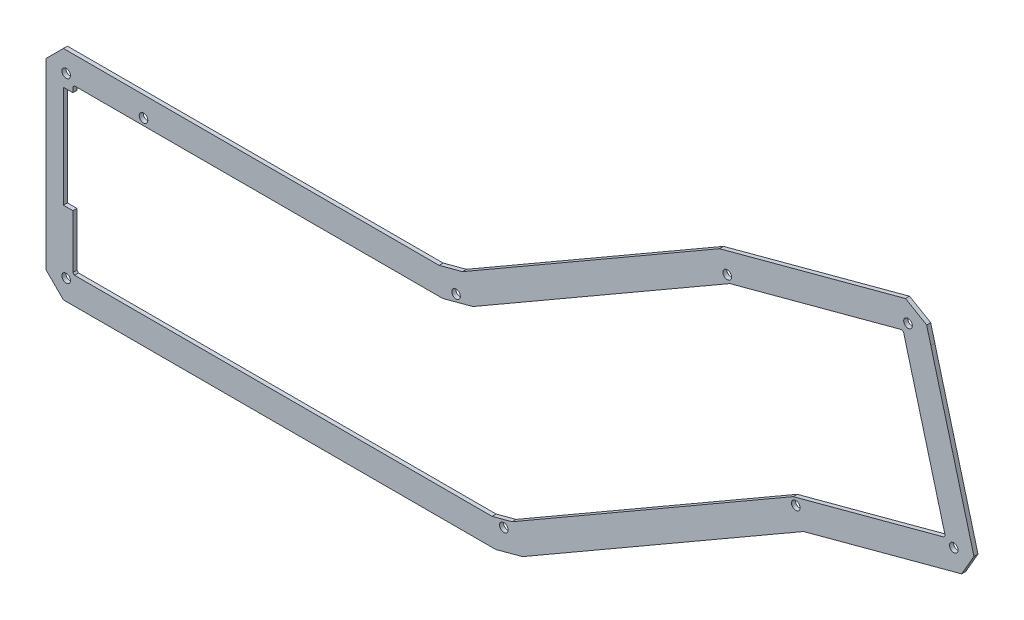
SolidWorks part; units mm, degrees
ref_plane "Plan de face" through (0, 0, 0) normal (0, 0, 1) x (1, 0, 0)
ref_plane "Plan de dessus" through (0, 0, 0) normal (0, 1, 0) x (1, 0, 0)
ref_plane "Plan de droite" through (0, 0, 0) normal (1, 0, 0) x (0, 0, -1)
sketch "Esquisse1" plane through (0, 0, 0) normal (0, 0, 1) x (1, 0, 0)
  line L0 (-73.9886, 18.0851) -> (-59.9886, 18.0851) construction
  line L1 (-73.9886, 37.0851) -> (-59.9886, 37.0851) construction
  line L2 (-73.9886, 37.0851) -> (-73.9886, 23.0851) construction
  line L3 (-73.9886, 23.0851) -> (-59.9886, 23.0851) construction
  line L4 (-59.9886, 37.0851) -> (-59.9886, 23.0851) construction
  line L5 (-73.9886, 18.0851) -> (-73.9886, 4.0851) construction
  line L6 (-73.9886, 4.0851) -> (-59.9886, 4.0851) construction
  line L7 (-59.9886, 18.0851) -> (-59.9886, 4.0851) construction
  line L8 (-73.9886, -0.9149) -> (-59.9886, -0.9149) construction
  line L9 (-73.9886, -0.9149) -> (-73.9886, -14.9149) construction
  line L10 (-73.9886, -14.9149) -> (-59.9886, -14.9149) construction
  line L11 (-59.9886, -0.9149) -> (-59.9886, -14.9149) construction
  line L12 (-73.9886, 37.0851) -> (-73.9886, 18.0851) construction
  line L13 (-54.9886, 18.0851) -> (-40.9886, 18.0851) construction
  line L14 (-54.9886, 37.0851) -> (-40.9886, 37.0851) construction
  line L15 (-54.9886, 37.0851) -> (-54.9886, 23.0851) construction
  line L16 (-54.9886, 23.0851) -> (-40.9886, 23.0851) construction
  line L17 (-40.9886, 37.0851) -> (-40.9886, 23.0851) construction
  line L18 (-54.9886, 18.0851) -> (-54.9886, 4.0851) construction
  line L19 (-54.9886, 4.0851) -> (-40.9886, 4.0851) construction
  line L20 (-40.9886, 18.0851) -> (-40.9886, 4.0851) construction
  line L21 (-54.9886, -0.9149) -> (-40.9886, -0.9149) construction
  line L22 (-54.9886, -0.9149) -> (-54.9886, -14.9149) construction
  line L23 (-54.9886, -14.9149) -> (-40.9886, -14.9149) construction
  line L24 (-40.9886, -0.9149) -> (-40.9886, -14.9149) construction
  line L25 (-54.9886, 37.0851) -> (-54.9886, 18.0851) construction
  line L26 (-35.9886, 18.0851) -> (-21.9886, 18.0851) construction
  line L27 (-35.9886, 37.0851) -> (-21.9886, 37.0851) construction
  line L28 (-35.9886, 37.0851) -> (-35.9886, 23.0851) construction
  line L29 (-35.9886, 23.0851) -> (-21.9886, 23.0851) construction
  line L30 (-21.9886, 37.0851) -> (-21.9886, 23.0851) construction
  line L31 (-35.9886, 18.0851) -> (-35.9886, 4.0851) construction
  line L32 (-35.9886, 4.0851) -> (-21.9886, 4.0851) construction
  line L33 (-21.9886, 18.0851) -> (-21.9886, 4.0851) construction
  line L34 (-35.9886, -0.9149) -> (-21.9886, -0.9149) construction
  line L35 (-35.9886, -0.9149) -> (-35.9886, -14.9149) construction
  line L36 (-35.9886, -14.9149) -> (-21.9886, -14.9149) construction
  line L37 (-21.9886, -0.9149) -> (-21.9886, -14.9149) construction
  line L38 (-35.9886, 37.0851) -> (-35.9886, 18.0851) construction
  line L39 (-16.9886, 18.0851) -> (-2.9886, 18.0851) construction
  line L40 (-16.9886, 37.0851) -> (-2.9886, 37.0851) construction
  line L41 (-16.9886, 37.0851) -> (-16.9886, 23.0851) construction
  line L42 (-16.9886, 23.0851) -> (-2.9886, 23.0851) construction
  line L43 (-2.9886, 37.0851) -> (-2.9886, 23.0851) construction
  line L44 (-16.9886, 18.0851) -> (-16.9886, 4.0851) construction
  line L45 (-16.9886, 4.0851) -> (-2.9886, 4.0851) construction
  line L46 (-2.9886, 18.0851) -> (-2.9886, 4.0851) construction
  line L47 (-16.9886, -0.9149) -> (-2.9886, -0.9149) construction
  line L48 (-16.9886, -0.9149) -> (-16.9886, -14.9149) construction
  line L49 (-16.9886, -14.9149) -> (-2.9886, -14.9149) construction
  line L50 (-2.9886, -0.9149) -> (-2.9886, -14.9149) construction
  line L51 (-16.9886, 37.0851) -> (-16.9886, 18.0851) construction
  line L52 (2.0114, 18.0851) -> (16.0114, 18.0851) construction
  line L53 (2.0114, 37.0851) -> (16.0114, 37.0851) construction
  line L54 (2.0114, 37.0851) -> (2.0114, 23.0851) construction
  line L55 (2.0114, 23.0851) -> (16.0114, 23.0851) construction
  line L56 (16.0114, 37.0851) -> (16.0114, 23.0851) construction
  line L57 (2.0114, 18.0851) -> (2.0114, 4.0851) construction
  line L58 (2.0114, 4.0851) -> (16.0114, 4.0851) construction
  line L59 (16.0114, 18.0851) -> (16.0114, 4.0851) construction
  line L60 (2.0114, -0.9149) -> (16.0114, -0.9149) construction
  line L61 (2.0114, -0.9149) -> (2.0114, -14.9149) construction
  line L62 (2.0114, -14.9149) -> (16.0114, -14.9149) construction
  line L63 (16.0114, -0.9149) -> (16.0114, -14.9149) construction
  line L64 (2.0114, 37.0851) -> (2.0114, 18.0851) construction
  line L65 (21.0114, 18.0851) -> (35.0114, 18.0851) construction
  line L66 (21.0114, 37.0851) -> (35.0114, 37.0851) construction
  line L67 (21.0114, 37.0851) -> (21.0114, 23.0851) construction
  line L68 (21.0114, 23.0851) -> (35.0114, 23.0851) construction
  line L69 (35.0114, 37.0851) -> (35.0114, 23.0851) construction
  line L70 (21.0114, 18.0851) -> (21.0114, 4.0851) construction
  line L71 (21.0114, 4.0851) -> (35.0114, 4.0851) construction
  line L72 (35.0114, 18.0851) -> (35.0114, 4.0851) construction
  line L73 (21.0114, -0.9149) -> (35.0114, -0.9149) construction
  line L74 (21.0114, -0.9149) -> (21.0114, -14.9149) construction
  line L75 (21.0114, -14.9149) -> (35.0114, -14.9149) construction
  line L76 (35.0114, -0.9149) -> (35.0114, -14.9149) construction
  line L77 (21.0114, 37.0851) -> (21.0114, 18.0851) construction
  line L78 (40.0114, 18.0851) -> (54.0114, 18.0851) construction
  line L79 (40.0114, 37.0851) -> (54.0114, 37.0851) construction
  line L80 (40.0114, 37.0851) -> (40.0114, 23.0851) construction
  line L81 (40.0114, 23.0851) -> (54.0114, 23.0851) construction
  line L82 (54.0114, 37.0851) -> (54.0114, 23.0851) construction
  line L83 (40.0114, 18.0851) -> (40.0114, 4.0851) construction
  line L84 (40.0114, 4.0851) -> (54.0114, 4.0851) construction
  line L85 (54.0114, 18.0851) -> (54.0114, 4.0851) construction
  line L86 (40.0114, -0.9149) -> (54.0114, -0.9149) construction
  line L87 (40.0114, -0.9149) -> (40.0114, -14.9149) construction
  line L88 (40.0114, -14.9149) -> (54.0114, -14.9149) construction
  line L89 (54.0114, -0.9149) -> (54.0114, -14.9149) construction
  line L90 (40.0114, 37.0851) -> (40.0114, 18.0851) construction
  line L91 (-73.9886, 18.0851) -> (-54.9886, 18.0851) construction
  line L92 (56.0114, 20.0851) -> (56.7532, 18.8002) construction
  line L93 (38.0114, 39.0851) -> (56.0114, 39.0851) construction
  line L94 (56.0114, 39.0851) -> (56.0114, 21.0851) construction
  line L95 (38.0114, 21.0851) -> (56.0114, 21.0851) construction
  line L96 (38.0114, 39.0851) -> (38.0114, 21.0851) construction
  line L97 (19.0114, 39.0851) -> (37.0114, 39.0851) construction
  line L98 (37.0114, 39.0851) -> (37.0114, 21.0851) construction
  line L99 (19.0114, 21.0851) -> (37.0114, 21.0851) construction
  line L100 (19.0114, 39.0851) -> (19.0114, 21.0851) construction
  line L101 (79.4363, 55.512) -> (88.4363, 39.9235) construction
  line L102 (88.4363, 39.9235) -> (72.8478, 30.9235) construction
  line L103 (63.8478, 46.512) -> (72.8478, 30.9235) construction
  line L104 (79.4363, 55.512) -> (63.8478, 46.512) construction
  line L105 (62.9818, 46.012) -> (71.9818, 30.4235) construction
  line L106 (71.9818, 30.4235) -> (56.3933, 21.4235) construction
  line L107 (47.3933, 37.012) -> (56.3933, 21.4235) construction
  line L108 (62.9818, 46.012) -> (47.3933, 37.012) construction
  line L109 (164.2542, 60.603) -> (148.6657, 51.603) construction
  line L110 (62.2497, 43.2799) -> (71.7497, 26.8254) construction
  line L111 (78.7042, 52.7799) -> (88.2042, 36.3254) construction
  line L112 (95.1587, 62.2799) -> (104.6587, 45.8254) construction
  line L113 (111.6132, 71.7799) -> (121.1132, 55.3254) construction
  line L114 (128.0677, 81.2799) -> (137.5677, 64.8254) construction
  line L115 (144.5221, 90.7799) -> (154.0221, 74.3254) construction
  line L116 (148.6657, 51.603) -> (157.6657, 36.0146) construction
  line L117 (69.1254, 3.371) -> (76.1254, -8.7534) construction
  line L118 (88.2497, -1.7534) -> (76.1254, -8.7534) construction
  line L119 (81.2497, 10.371) -> (88.2497, -1.7534) construction
  line L120 (81.2497, 10.371) -> (69.1254, 3.371) construction
  line L121 (59.6254, 19.8254) -> (66.6254, 7.7011) construction
  line L122 (78.7497, 14.7011) -> (66.6254, 7.7011) construction
  line L123 (71.7497, 26.8254) -> (78.7497, 14.7011) construction
  line L124 (50.1254, 36.2799) -> (57.1254, 24.1556) construction
  line L125 (69.2497, 31.1556) -> (57.1254, 24.1556) construction
  line L126 (62.2497, 43.2799) -> (69.2497, 31.1556) construction
  line L127 (62.2497, 43.2799) -> (50.1254, 36.2799) construction
  line L128 (71.7497, 26.8254) -> (59.6254, 19.8254) construction
  line L129 (85.5799, 12.871) -> (92.5799, 0.7466) construction
  line L130 (104.7042, 7.7466) -> (92.5799, 0.7466) construction
  line L131 (97.7042, 19.871) -> (104.7042, 7.7466) construction
  line L132 (97.7042, 19.871) -> (85.5799, 12.871) construction
  line L133 (76.0799, 29.3254) -> (83.0799, 17.2011) construction
  line L134 (95.2042, 24.2011) -> (83.0799, 17.2011) construction
  line L135 (88.2042, 36.3254) -> (95.2042, 24.2011) construction
  line L136 (66.5799, 45.7799) -> (73.5799, 33.6556) construction
  line L137 (85.7042, 40.6556) -> (73.5799, 33.6556) construction
  line L138 (78.7042, 52.7799) -> (85.7042, 40.6556) construction
  line L139 (78.7042, 52.7799) -> (66.5799, 45.7799) construction
  line L140 (88.2042, 36.3254) -> (76.0799, 29.3254) construction
  line L141 (102.0343, 22.371) -> (109.0343, 10.2466) construction
  line L142 (121.1587, 17.2466) -> (109.0343, 10.2466) construction
  line L143 (114.1587, 29.371) -> (121.1587, 17.2466) construction
  line L144 (114.1587, 29.371) -> (102.0343, 22.371) construction
  line L145 (92.5343, 38.8254) -> (99.5343, 26.7011) construction
  line L146 (111.6587, 33.7011) -> (99.5343, 26.7011) construction
  line L147 (104.6587, 45.8254) -> (111.6587, 33.7011) construction
  line L148 (83.0343, 55.2799) -> (90.0343, 43.1556) construction
  line L149 (102.1587, 50.1556) -> (90.0343, 43.1556) construction
  line L150 (95.1587, 62.2799) -> (102.1587, 50.1556) construction
  line L151 (95.1587, 62.2799) -> (83.0343, 55.2799) construction
  line L152 (104.6587, 45.8254) -> (92.5343, 38.8254) construction
  line L153 (118.4888, 31.871) -> (125.4888, 19.7466) construction
  line L154 (137.6132, 26.7466) -> (125.4888, 19.7466) construction
  line L155 (130.6132, 38.871) -> (137.6132, 26.7466) construction
  line L156 (130.6132, 38.871) -> (118.4888, 31.871) construction
  line L157 (108.9888, 48.3254) -> (115.9888, 36.2011) construction
  line L158 (128.1132, 43.2011) -> (115.9888, 36.2011) construction
  line L159 (121.1132, 55.3254) -> (128.1132, 43.2011) construction
  line L160 (99.4888, 64.7799) -> (106.4888, 52.6556) construction
  line L161 (118.6132, 59.6556) -> (106.4888, 52.6556) construction
  line L162 (111.6132, 71.7799) -> (118.6132, 59.6556) construction
  line L163 (111.6132, 71.7799) -> (99.4888, 64.7799) construction
  line L164 (121.1132, 55.3254) -> (108.9888, 48.3254) construction
  line L165 (134.9433, 41.371) -> (141.9433, 29.2466) construction
  line L166 (154.0677, 36.2466) -> (141.9433, 29.2466) construction
  line L167 (147.0677, 48.371) -> (154.0677, 36.2466) construction
  line L168 (147.0677, 48.371) -> (134.9433, 41.371) construction
  line L169 (125.4433, 57.8254) -> (132.4433, 45.7011) construction
  line L170 (144.5677, 52.7011) -> (132.4433, 45.7011) construction
  line L171 (137.5677, 64.8254) -> (144.5677, 52.7011) construction
  line L172 (115.9433, 74.2799) -> (122.9433, 62.1556) construction
  line L173 (135.0677, 69.1556) -> (122.9433, 62.1556) construction
  line L174 (128.0677, 81.2799) -> (135.0677, 69.1556) construction
  line L175 (128.0677, 81.2799) -> (115.9433, 74.2799) construction
  line L176 (137.5677, 64.8254) -> (125.4433, 57.8254) construction
  line L177 (151.3978, 50.871) -> (158.3978, 38.7466) construction
  line L178 (170.5221, 45.7466) -> (158.3978, 38.7466) construction
  line L179 (163.5221, 57.871) -> (170.5221, 45.7466) construction
  line L180 (163.5221, 57.871) -> (151.3978, 50.871) construction
  line L181 (141.8978, 67.3254) -> (148.8978, 55.2011) construction
  line L182 (161.0221, 62.2011) -> (148.8978, 55.2011) construction
  line L183 (154.0221, 74.3254) -> (161.0221, 62.2011) construction
  line L184 (132.3978, 83.7799) -> (139.3978, 71.6556) construction
  line L185 (151.5221, 78.6556) -> (139.3978, 71.6556) construction
  line L186 (144.5221, 90.7799) -> (151.5221, 78.6556) construction
  line L187 (144.5221, 90.7799) -> (132.3978, 83.7799) construction
  line L188 (154.0221, 74.3254) -> (141.8978, 67.3254) construction
  line L189 (173.2542, 45.0146) -> (157.6657, 36.0146) construction
  line L190 (164.2542, 60.603) -> (173.2542, 45.0146) construction
  line L191 (178.3169, 34.0986) -> (169.0534, 56.4627) construction
  line L192 (169.5193, 62.7839) -> (174.1781, 45.3972) construction
  line L193 (174.1781, 45.3972) -> (191.5647, 50.056) construction
  line L194 (186.906, 67.4426) -> (191.5647, 50.056) construction
  line L195 (162.1337, 98.0749) -> (167.0513, 79.7223) construction
  line L196 (169.5193, 62.7839) -> (186.906, 67.4426) construction
  line L197 (167.0513, 79.7223) -> (180.5742, 83.3457) construction
  line L198 (162.1337, 98.0749) -> (175.6567, 101.6983) construction
  line L199 (162.1337, 98.0749) -> (165.7572, 84.5519) construction
  line L200 (165.7572, 84.5519) -> (179.2801, 88.1754) construction
  line L201 (175.6567, 101.6983) -> (179.2801, 88.1754) construction
  line L202 (167.0513, 79.7223) -> (170.6747, 66.1993) construction
  line L203 (170.6747, 66.1993) -> (184.1977, 69.8228) construction
  line L204 (180.5742, 83.3457) -> (184.1977, 69.8228) construction
  line L205 (171.9688, 61.3697) -> (185.4918, 64.9932) construction
  line L206 (171.9688, 61.3697) -> (175.5923, 47.8467) construction
  line L207 (175.5923, 47.8467) -> (189.1152, 51.4702) construction
  line L208 (185.4918, 64.9932) -> (189.1152, 51.4702) construction
  line L209 (185.4038, 84.6398) -> (198.9268, 88.2633) construction
  line L210 (180.4863, 102.9924) -> (194.0092, 106.6159) construction
  line L211 (180.4863, 102.9924) -> (184.1097, 89.4695) construction
  line L212 (184.1097, 89.4695) -> (197.6327, 93.0929) construction
  line L213 (194.0092, 106.6159) -> (197.6327, 93.0929) construction
  line L214 (185.4038, 84.6398) -> (189.0273, 71.1169) construction
  line L215 (189.0273, 71.1169) -> (202.5503, 74.7403) construction
  line L216 (198.9268, 88.2633) -> (202.5503, 74.7403) construction
  line L217 (190.3214, 66.2873) -> (203.8444, 69.9107) construction
  line L218 (190.3214, 66.2873) -> (193.9449, 52.7643) construction
  line L219 (193.9449, 52.7643) -> (207.4678, 56.3878) construction
  line L220 (203.8444, 69.9107) -> (207.4678, 56.3878) construction
  line L221 (187.8719, 67.7015) -> (192.5307, 50.3148) construction
  line L222 (192.5307, 50.3148) -> (209.9173, 54.9735) construction
  line L223 (205.2586, 72.3602) -> (209.9173, 54.9735) construction
  line L224 (180.4863, 102.9924) -> (185.4038, 84.6398) construction
  line L225 (187.8719, 67.7015) -> (205.2586, 72.3602) construction
  line L226 (203.7564, 89.5574) -> (217.2794, 93.1809) construction
  line L227 (198.8389, 107.91) -> (212.3618, 111.5335) construction
  line L228 (198.8389, 107.91) -> (202.4623, 94.387) construction
  line L229 (202.4623, 94.387) -> (215.9853, 98.0105) construction
  line L230 (212.3618, 111.5335) -> (215.9853, 98.0105) construction
  line L231 (203.7564, 89.5574) -> (207.3799, 76.0344) construction
  line L232 (207.3799, 76.0344) -> (220.9029, 79.6579) construction
  line L233 (217.2794, 93.1809) -> (220.9029, 79.6579) construction
  line L234 (208.674, 71.2048) -> (222.197, 74.8283) construction
  line L235 (208.674, 71.2048) -> (212.2975, 57.6819) construction
  line L236 (212.2975, 57.6819) -> (225.8204, 61.3053) construction
  line L237 (222.197, 74.8283) -> (225.8204, 61.3053) construction
  line L238 (206.2245, 72.619) -> (210.8833, 55.2324) construction
  line L239 (210.8833, 55.2324) -> (228.2699, 59.8911) construction
  line L240 (223.6112, 77.2778) -> (228.2699, 59.8911) construction
  line L241 (198.8389, 107.91) -> (203.7564, 89.5574) construction
  line L242 (206.2245, 72.619) -> (223.6112, 77.2778) construction
  line L243 (167.0513, 79.7223) -> (185.4038, 84.6398) construction
  line L244 (38.0114, 20.0851) -> (56.0114, 20.0851) construction
  line L245 (56.0114, 20.0851) -> (56.0114, 2.0851) construction
  line L246 (38.0114, 2.0851) -> (56.0114, 2.0851) construction
  line L247 (38.0114, 20.0851) -> (38.0114, 2.0851) construction
  line L248 (72.4818, 29.5575) -> (56.8933, 20.5575) construction
  line L249 (56.8933, 20.5575) -> (65.8933, 4.969) construction
  line L250 (81.4818, 13.969) -> (65.8933, 4.969) construction
  line L251 (72.4818, 29.5575) -> (81.4818, 13.969) construction
  line L252 (56.8933, 20.5575) -> (57.6111, 19.3142) construction
  line L253 (164.6018, 81.1365) -> (169.2605, 63.7498) construction
  line L254 (169.2605, 63.7498) -> (186.6472, 68.4086) construction
  line L255 (181.9884, 85.7952) -> (186.6472, 68.4086) construction
  line L256 (164.6018, 81.1365) -> (181.9884, 85.7952) construction
  line L257 (154.7542, 77.0575) -> (163.7542, 61.469) construction
  line L258 (163.7542, 61.469) -> (148.1657, 52.469) construction
  line L259 (139.1657, 68.0575) -> (148.1657, 52.469) construction
  line L260 (154.7542, 77.0575) -> (139.1657, 68.0575) construction
  line L261 (196.3894, 109.3242) -> (213.776, 113.983) construction
  line L262 (-94.7538, 35.7952) -> (-76.7538, 35.7952) construction
  line L263 (-94.7538, 35.7952) -> (-94.7538, 2.7952) construction
  line L264 (-94.7538, 2.7952) -> (-76.7538, 2.7952) construction
  line L265 (-76.7538, 35.7952) -> (-76.7538, 2.7952) construction
  line L266 (213.776, 113.983) -> (218.4348, 96.5963) construction
  line L267 (201.0481, 91.9375) -> (218.4348, 96.5963) construction
  line L268 (196.3894, 109.3242) -> (201.0481, 91.9375) construction
  line L269 (-75.9886, -16.9149) -> (-57.9886, -16.9149) construction
  line L270 (-57.9886, 1.0851) -> (-57.9886, -16.9149) construction
  line L271 (-75.9886, 1.0851) -> (-57.9886, 1.0851) construction
  line L272 (-75.9886, 1.0851) -> (-75.9886, -16.9149) construction
  line L273 (38.0114, -16.9149) -> (56.0114, -16.9149) construction
  line L274 (56.0114, 1.0851) -> (56.0114, -16.9149) construction
  line L275 (38.0114, 1.0851) -> (56.0114, 1.0851) construction
  line L276 (38.0114, 1.0851) -> (38.0114, -16.9149) construction
  line L277 (-75.9886, 39.0851) -> (-57.9886, 39.0851) construction
  line L278 (-57.9886, 39.0851) -> (-57.9886, 21.0851) construction
  line L279 (-75.9886, 21.0851) -> (-57.9886, 21.0851) construction
  line L280 (-75.9886, 39.0851) -> (-75.9886, 21.0851) construction
  line L281 (145.2542, 93.512) -> (129.6657, 84.512) construction
  line L282 (129.6657, 84.512) -> (138.6657, 68.9235) construction
  line L283 (154.2542, 77.9235) -> (138.6657, 68.9235) construction
  line L284 (145.2542, 93.512) -> (154.2542, 77.9235) construction
  line L285 (223.4353, 116.5711) -> (228.0941, 99.1845) construction
  line L286 (148.2159, 106.7689) -> (211.1879, 123.6422) construction
  line L287 (177.5508, 35.9482) -> (235.6877, 51.5259) construction
  line L288 (177.5508, 35.9482) -> (72.9989, -24.4149) construction
  line L289 (-95.7538, -26.9149) -> (63.6687, -26.9149) construction
  line L290 (-100.7538, 35.7952) -> (-100.7538, -21.9149) construction
  line L291 (-75.9886, 49.0851) -> (43.3046, 49.0851) construction
  line L292 (148.2159, 106.7689) -> (52.6347, 51.5851) construction
  line L293 (-75.9886, 49.0851) -> (-57.9886, 49.0851) construction
  line L294 (140.2542, 102.1722) -> (124.6657, 93.1722) construction
  line L295 (193.8012, 118.9835) -> (211.1879, 123.6422) construction
  line L296 (213.4714, 45.5731) -> (230.8581, 50.2318) construction
  line L297 (38.0114, -26.9149) -> (38.0114, -85.4624) construction
  line L298 (178.2542, 36.3543) -> (162.6657, 27.3543) construction
  line L299 (38.0114, -26.9149) -> (56.0114, -26.9149) construction
  line L300 (-100.7538, 2.7952) -> (-100.7538, -38.0419) construction
  line L301 (-100.7538, 35.7952) -> (-100.7538, 2.7952) construction
  line L302 (-75.9886, 49.0851) -> (-95.7538, 49.0851) construction
  line L303 (-100.7538, 44.0851) -> (-100.7538, 35.7952) construction
  line L304 (211.1879, 123.6422) -> (216.0732, 124.9512) construction
  line L305 (222.1691, 121.4083) -> (223.4353, 116.5711) construction
  line L306 (228.0941, 99.1845) -> (239.2233, 57.6497) construction
  line L307 (216.0732, 124.9512) -> (222.1691, 121.4083) construction
  line L308 (235.6877, 51.5259) -> (239.2233, 57.6497) construction
  line L309 (63.6687, -26.9149) -> (72.9989, -24.4149) construction
  line L310 (52.6347, 51.5851) -> (43.3046, 49.0851) construction
  line L311 (-95.7538, 49.0851) -> (-100.7538, 44.0851) construction
  line L312 (-100.7538, -21.9149) -> (-95.7538, -26.9149) construction
  line L313 (-95.7538, 49.0851) -> (-95.7538, 44.0851) construction
  line L314 (-95.7538, 44.0851) -> (-100.7538, 44.0851) construction
  line L315 (-95.7538, -26.9149) -> (-95.7538, -21.9149) construction
  line L316 (68.3338, -25.6649) -> (67.0397, -20.8353) construction
  line L317 (47.9697, 50.3351) -> (49.2637, 45.5055) construction
  line L318 (177.5508, 35.9482) -> (175.6374, 40.5676) construction
  line L319 (148.2159, 106.7689) -> (150.1293, 102.1495) construction
  line L320 (239.2233, 57.6497) -> (234.3936, 56.3556) construction
  line L321 (216.0732, 124.9512) -> (217.3634, 120.1206) construction
  line L322 (-66.9886, 37.0851) -> (-66.9886, 49.0851) construction
  line L323 (-76.7538, 35.7952) -> (-96.7538, 35.7952) construction
  line L324 (-95.7538, 44.0851) -> (-65.1374, 44.0851) construction
  line L325 (-93.2538, 39.0851) -> (-96.7538, 39.0851)
  line L327 (-93.2538, 1.0851) -> (-96.7538, 1.0851)
  line L328 (-96.7538, 39.0851) -> (-96.7538, 1.0851)
  line L329 (-75.9886, 50.5851) -> (43.1071, 50.5851) construction
  line L330 (52.0557, 52.9829) -> (43.1071, 50.5851) construction
  line L331 (147.6369, 108.1667) -> (52.0557, 52.9829) construction
  line L332 (147.6369, 108.1667) -> (210.7996, 125.0911) construction
  line L333 (210.7996, 125.0911) -> (216.2876, 126.5616) construction
  line L334 (216.2876, 126.5616) -> (223.4622, 122.3917) construction
  line L335 (223.4622, 122.3917) -> (224.8853, 116.9552) construction
  line L336 (224.8853, 116.9552) -> (229.5429, 99.5727) construction
  line L337 (229.5429, 99.5727) -> (240.833, 57.4377) construction
  line L338 (236.6761, 50.2379) -> (240.833, 57.4377) construction
  line L339 (178.1298, 34.5504) -> (236.6761, 50.2379) construction
  line L340 (178.1298, 34.5504) -> (73.5778, -25.8127) construction
  line L341 (63.8662, -28.4149) -> (73.5778, -25.8127) construction
  line L342 (-96.3751, -28.4149) -> (63.8662, -28.4149) construction
  line L343 (-102.2538, -22.5362) -> (-96.3751, -28.4149) construction
  line L344 (-102.2538, 35.7952) -> (-102.2538, -22.5362) construction
  line L345 (-102.2538, 44.7064) -> (-102.2538, 35.7952) construction
  line L346 (-96.3751, 50.5851) -> (-102.2538, 44.7064) construction
  line L347 (-75.9886, 50.5851) -> (-96.3751, 50.5851) construction
  line L348 (-75.9886, 52.5851) -> (42.8438, 52.5851) construction
  line L349 (51.2838, 54.8466) -> (42.8438, 52.5851) construction
  line L350 (146.8649, 110.0304) -> (51.2838, 54.8466) construction
  line L351 (146.8649, 110.0304) -> (210.282, 127.023) construction
  line L352 (210.282, 127.023) -> (216.5734, 128.7087) construction
  line L353 (216.5734, 128.7087) -> (225.1863, 123.7029) construction
  line L354 (225.1863, 123.7029) -> (226.8187, 117.4673) construction
  line L355 (226.8187, 117.4673) -> (231.4748, 100.0903) construction
  line L356 (231.4748, 100.0903) -> (242.9792, 57.1552) construction
  line L357 (237.994, 48.5204) -> (242.9792, 57.1552) construction
  line L358 (178.9017, 32.6867) -> (237.994, 48.5204) construction
  line L359 (178.9017, 32.6867) -> (74.3498, -27.6764) construction
  line L360 (64.1295, -30.4149) -> (74.3498, -27.6764) construction
  line L361 (-97.2035, -30.4149) -> (64.1295, -30.4149) construction
  line L362 (-104.2538, -23.3646) -> (-97.2035, -30.4149) construction
  line L363 (-104.2538, 35.7952) -> (-104.2538, -23.3646) construction
  line L364 (-104.2538, 45.5349) -> (-104.2538, 35.7952) construction
  line L365 (-97.2035, 52.5851) -> (-104.2538, 45.5349) construction
  line L366 (-75.9886, 52.5851) -> (-97.2035, 52.5851) construction
  line L367 (-75.9886, 51.5851) -> (42.9755, 51.5851)
  line L368 (51.6698, 53.9147) -> (42.9755, 51.5851)
  line L369 (147.2509, 109.0986) -> (51.6698, 53.9147)
  line L370 (147.2509, 109.0986) -> (210.5408, 126.057)
  line L371 (210.5408, 126.057) -> (216.4305, 127.6352)
  line L372 (216.4305, 127.6352) -> (224.3243, 123.0473)
  line L373 (224.3243, 123.0473) -> (225.852, 117.2112)
  line L374 (225.852, 117.2112) -> (230.5089, 99.8315)
  line L375 (230.5089, 99.8315) -> (241.9061, 57.2965)
  line L376 (237.335, 49.3791) -> (241.9061, 57.2965)
  line L377 (178.5158, 33.6186) -> (237.335, 49.3791)
  line L378 (178.5158, 33.6186) -> (73.9638, -26.7445)
  line L379 (63.9979, -29.4149) -> (73.9638, -26.7445)
  line L380 (-96.7893, -29.4149) -> (63.9979, -29.4149)
  line L381 (-103.2538, -22.9504) -> (-96.7893, -29.4149)
  line L382 (-103.2538, 35.7952) -> (-103.2538, -22.9504)
  line L383 (-103.2538, 45.1206) -> (-103.2538, 35.7952)
  line L384 (-96.7893, 51.5851) -> (-103.2538, 45.1206)
  line L385 (-75.9886, 51.5851) -> (-96.7893, 51.5851)
  line L386 (-75.9886, 41.5851) -> (-92.6472, 41.5851)
  line L387 (-92.6472, 41.5851) -> (-93.2538, 40.9785)
  line L388 (-93.2538, 40.9785) -> (-93.2538, 39.0851)
  line L389 (-93.2538, 1.0851) -> (-93.2538, -18.8083)
  line L390 (-93.2538, -18.8083) -> (-92.6472, -19.4149)
  line L391 (-92.6472, -19.4149) -> (62.6813, -19.4149)
  line L392 (62.6813, -19.4149) -> (70.104, -17.426)
  line L393 (174.6559, 42.9371) -> (70.104, -17.426)
  line L394 (174.6559, 42.9371) -> (230.7458, 57.9663)
  line L395 (230.7458, 57.9663) -> (231.1748, 58.7093)
  line L396 (220.8496, 97.2433) -> (231.1748, 58.7093)
  line L397 (216.1853, 114.6509) -> (220.8496, 97.2433)
  line L398 (215.7035, 116.4914) -> (216.1853, 114.6509)
  line L399 (215.0014, 116.8995) -> (215.7035, 116.4914)
  line L400 (213.129, 116.3978) -> (215.0014, 116.8995)
  line L401 (151.1108, 99.78) -> (213.129, 116.3978)
  line L402 (151.1108, 99.78) -> (55.5296, 44.5962)
  line L403 (55.5296, 44.5962) -> (44.292, 41.5851)
  line L404 (-75.9886, 41.5851) -> (44.292, 41.5851)
  line L406 (-93.2538, 35.7952) -> (-93.2538, -18.8083) construction
  line L407 (-93.2538, 40.9785) -> (-93.2538, 35.7952) construction
  circle A0 centre (-95.7538, 44.0851) radius 1.5 construction
  circle A1 centre (-95.7538, -21.9149) radius 1.5 construction
  circle A2 centre (67.0397, -20.8353) radius 1.5 construction
  circle A3 centre (49.2637, 45.5055) radius 1.5 construction
  circle A4 centre (175.6374, 40.5676) radius 1.5 construction
  circle A5 centre (150.1293, 102.1495) radius 1.5 construction
  circle A6 centre (234.3936, 56.3556) radius 1.5 construction
  circle A7 centre (217.3634, 120.1206) radius 1.5 construction
  circle A8 centre (-66.9886, 44.0851) radius 1.5 construction
  circle A9 centre (-95.7538, 44.0851) radius 1.6
  circle A10 centre (-66.9886, 44.0851) radius 1.6
  circle A11 centre (-95.7538, -21.9149) radius 1.6
  circle A12 centre (67.0397, -20.8353) radius 1.6
  circle A13 centre (49.2637, 45.5055) radius 1.6
  circle A14 centre (175.6374, 40.5676) radius 1.6
  circle A15 centre (150.1293, 102.1495) radius 1.6
  circle A16 centre (217.3634, 120.1206) radius 1.6
  circle A17 centre (234.3936, 56.3556) radius 1.6
  point P304 (48.3046, 49.0851)
  point P305 (240.5174, 52.82)
  point P308 (68.6687, -26.9149)
  point P309 (-100.7538, -26.9149)
  point P311 (-100.7538, 49.0851)
  point P312 (220.9029, 126.2453)
  dimension "D32" = 3
  dimension "D33" = 5
  dimension "D40" = 5
  dimension "D41" = 5
  dimension "D42" = 5
  dimension "D43" = 5
  dimension "D44" = 20
  dimension "D45" = 1.5
  dimension "D49" = 0.1
  dimension "D1" = 14
  dimension "D2" = 14
  dimension "D4" = 19
  dimension "D6" = 19
  dimension "D7" = 30
  dimension "D10" = 1
  dimension "D11" = 2
  dimension "D13" = 0.5
  dimension "D15" = 2
  dimension "D12" = 7.5
  dimension "D14" = 19
  dimension "D18" = 2
  dimension "D20" = 18
  dimension "D21" = 33
  dimension "D22" = 2
  dimension "D8" = 2
  dimension "D9" = 2
  dimension "D16" = 2
  dimension "D19" = 2
  dimension "D23" = 2
  dimension "D24" = 10
  dimension "D25" = 10
  dimension "D26" = 10
  dimension "D27" = 10
  dimension "D28" = 10
  dimension "D29" = 6
  dimension "D30" = 10
  dimension "D31" = 10
  dimension "D46" = 2
  dimension "D47" = 1
  dimension "D48" = 0.1
  dimension "D50" = 10
  dimension "D3" = 3
  dimension "D5" = 7
  dimension "D17" = 3
extrude "Boss.-Extru.1" add sketch "Esquisse1" along normal blind 1.5
